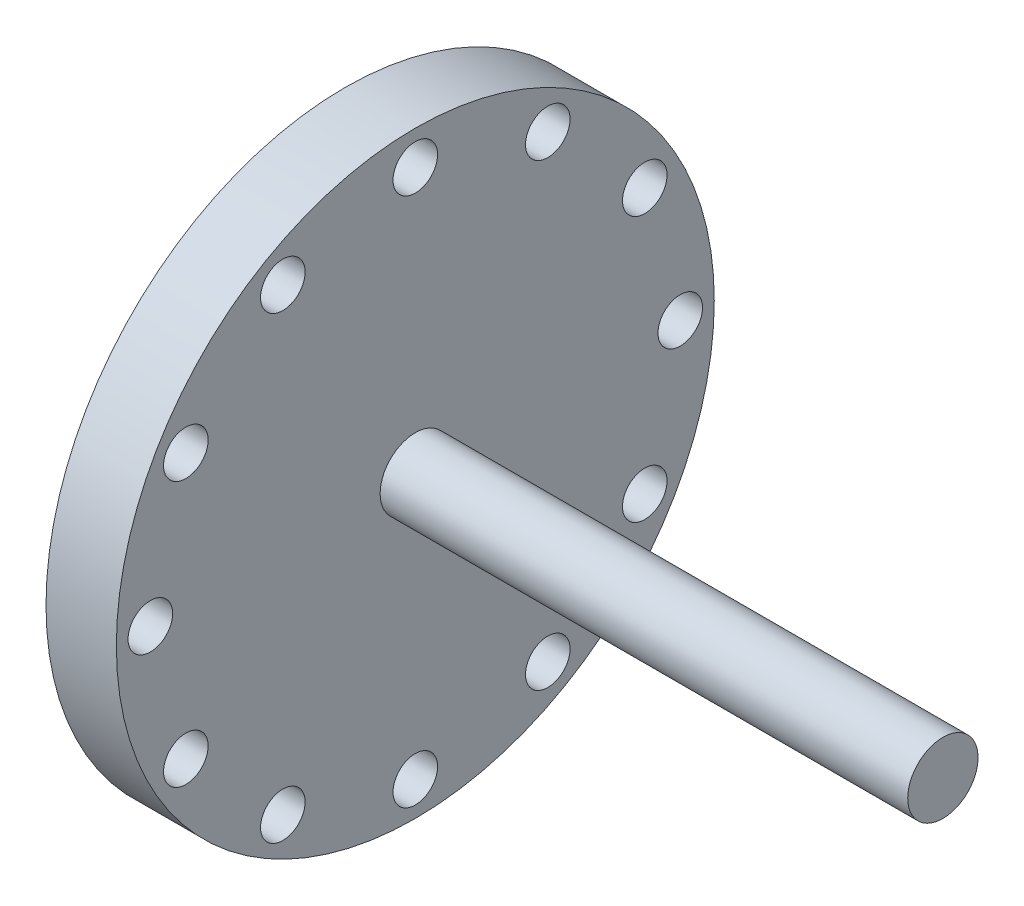
SolidWorks part; units mm, degrees
ref_plane "Спереди" through (0, 0, 0) normal (0, 0, 1) x (1, 0, 0)
ref_plane "Сверху" through (0, 0, 0) normal (0, 1, 0) x (1, 0, 0)
ref_plane "Справа" through (0, 0, 0) normal (1, 0, 0) x (0, 0, -1)
sketch "Эскиз1" plane through (0, 0, 0) normal (0, 0, 1) x (1, 0, 0)
  line L0 (0, 0) -> (265, 0)
  line L1 (0, 0) -> (0, 20)
  line L2 (0, 20) -> (10, 20)
  line L3 (10, 20) -> (10, 127.5)
  line L4 (10, 127.5) -> (40, 127.5)
  line L5 (40, 127.5) -> (40, 15)
  line L6 (40, 15) -> (265, 15)
  line L7 (265, 15) -> (265, 0)
revolve "Повернуть1" add sketch "Эскиз1" angle 360 about L0
sketch "Эскиз2" plane through (0, 0, 0) normal (1, 0, 0) x (0, 0, -1)
  circle A0 centre (0, 113) radius 9.5
extrude "Вырез-Вытянуть1" cut sketch "Эскиз2" along normal through all
sketch "Эскиз3" plane through (0, 0, 0) normal (1, 0, 0) x (0, 0, -1)
  circle A0 centre (-56.5, 97.8609) radius 9.5
extrude "Вырез-Вытянуть2" cut sketch "Эскиз3" along normal through all
sketch "Эскиз4" plane through (0, 0, 0) normal (1, 0, 0) x (0, 0, -1)
  circle A0 centre (-97.8609, 56.5) radius 9.5
extrude "Вырез-Вытянуть3" cut sketch "Эскиз4" along normal through all
sketch "Эскиз5" plane through (0, 0, 0) normal (1, 0, 0) x (0, 0, -1)
  circle A0 centre (-113, 0) radius 9.5
extrude "Вырез-Вытянуть4" cut sketch "Эскиз5" along normal through all
sketch "Эскиз6" plane through (0, 0, 0) normal (1, 0, 0) x (0, 0, -1)
  circle A0 centre (-97.8609, -56.5) radius 9.5
extrude "Вырез-Вытянуть5" cut sketch "Эскиз6" along normal through all
sketch "Эскиз7" plane through (0, 0, 0) normal (1, 0, 0) x (0, 0, -1)
  circle A0 centre (-56.5, -97.8609) radius 9.5
extrude "Вырез-Вытянуть6" cut sketch "Эскиз7" along normal through all
sketch "Эскиз8" plane through (0, 0, 0) normal (1, 0, 0) x (0, 0, -1)
  circle A0 centre (0, -113) radius 9.5
extrude "Вырез-Вытянуть7" cut sketch "Эскиз8" along normal through all
sketch "Эскиз9" plane through (0, 0, 0) normal (1, 0, 0) x (0, 0, -1)
  circle A0 centre (56.5, -97.8609) radius 9.5
extrude "Вырез-Вытянуть8" cut sketch "Эскиз9" along normal through all
sketch "Эскиз10" plane through (0, 0, 0) normal (1, 0, 0) x (0, 0, -1)
  circle A0 centre (97.8609, -56.5) radius 9.5
extrude "Вырез-Вытянуть9" cut sketch "Эскиз10" along normal through all
sketch "Эскиз11" plane through (0, 0, 0) normal (1, 0, 0) x (0, 0, -1)
  circle A0 centre (113, 0) radius 9.5
extrude "Вырез-Вытянуть10" cut sketch "Эскиз11" along normal through all
sketch "Эскиз12" plane through (0, 0, 0) normal (1, 0, 0) x (0, 0, -1)
  circle A0 centre (97.8609, 56.5) radius 9.5
extrude "Вырез-Вытянуть11" cut sketch "Эскиз12" along normal through all
sketch "Эскиз13" plane through (0, 0, 0) normal (1, 0, 0) x (0, 0, -1)
  circle A0 centre (56.5, 97.8609) radius 9.5
extrude "Вырез-Вытянуть12" cut sketch "Эскиз13" along normal through all
